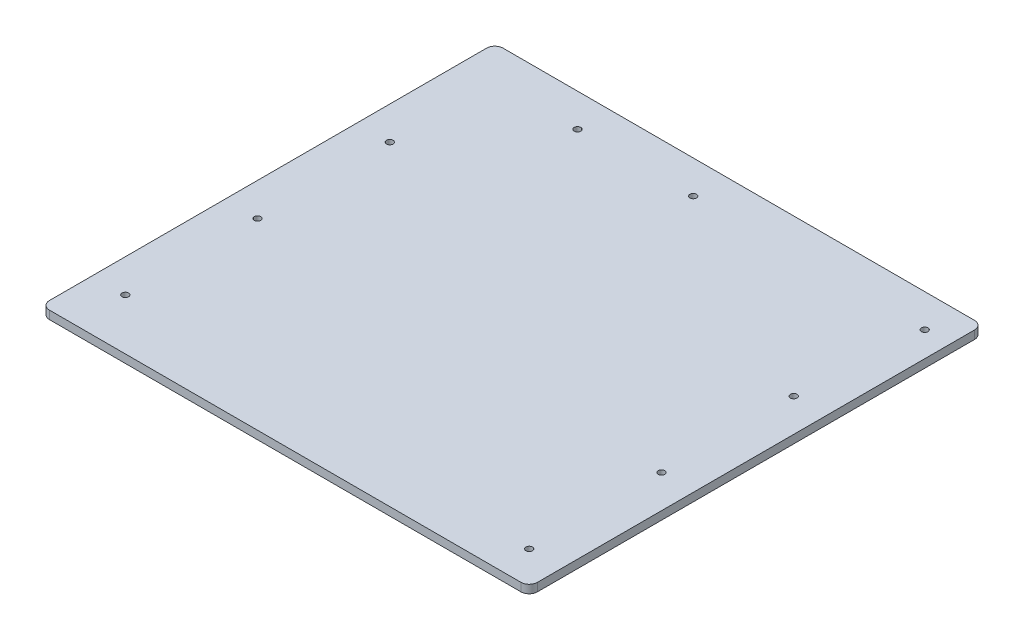
SolidWorks part; units mm, degrees
ref_plane "Front Plane" through (0, 0, 0) normal (0, 0, 1) x (1, 0, 0)
ref_plane "Top Plane" through (0, 0, 0) normal (0, 1, 0) x (1, 0, 0)
ref_plane "Right Plane" through (0, 0, 0) normal (1, 0, 0) x (0, 0, -1)
sketch "Sketch1" plane through (0, 0, 0) normal (0, 1, 0) x (1, 0, 0)
  line L0 (-81.026, -67.4929) -> (-81.026, -16.6929) construction
  line L1 (-93.726, -87.122) -> (93.726, -87.122)
  line L2 (-93.726, -87.122) -> (-93.726, 87.122)
  line L3 (-93.726, 87.122) -> (93.726, 87.122)
  line L4 (93.726, -87.122) -> (93.726, 87.122)
  line L5 (-93.726, -87.122) -> (93.726, 87.122) construction
  line L6 (-93.726, 87.122) -> (93.726, -87.122) construction
  line L7 (0, -1000) -> (0, 49000) construction
  circle A0 centre (-81.026, -67.4929) radius 1.27
  circle A1 centre (-81.026, -16.6929) radius 1.27
  circle A2 centre (-81.026, 34.1071) radius 1.27
  circle A3 centre (-4.826, 74.422) radius 1.27
  circle A4 centre (84.074, 74.422) radius 1.27
  circle A7 centre (-49.276, 74.422) radius 1.27
  point P0 (0, 0)
  point P22 (0, 0)
  dimension "D7" = 88.9
  dimension "D8" = 88.9
  dimension "D10" = 2.54
  dimension "D1" = 174.244
  dimension "D2" = 187.452
  dimension "D3" = 19.6291
  dimension "D4" = 12.7
  dimension "D6" = 50.8
  dimension "D9" = 12.7
  dimension "D11" = 44.45
  dimension "D5" = 3
extrude "Boss-Extrude1" add sketch "Sketch1" along normal blind 3.175
sketch "Sketch2" plane through (0, 3.175, 0) normal (0, 1, 0) x (1, 0, 0)
  line L0 (-93.726, -87.122) -> (93.726, -87.122) construction
  line L1 (93.726, -87.122) -> (93.726, 87.122) construction
  line L2 (81.026, -74.422) -> (81.026, -23.622) construction
  circle A2 centre (81.026, -74.422) radius 1.27
  circle A3 centre (81.026, -23.622) radius 1.27
  circle A4 centre (81.026, 27.178) radius 1.27
  dimension "D1" = 2.54
  dimension "D2" = 3
  dimension "D3" = 50.8
  dimension "D4" = 12.7
  dimension "D5" = 12.7
extrude "Cut-Extrude3" cut sketch "Sketch2" against normal through all
fillet "Fillet1" radius 3.175 4 edges at (93.726, 1.5875, 87.122) (-93.726, 1.5875, -87.122) (93.726, 1.5875, -87.122) (-93.726, 1.5875, 87.122)
